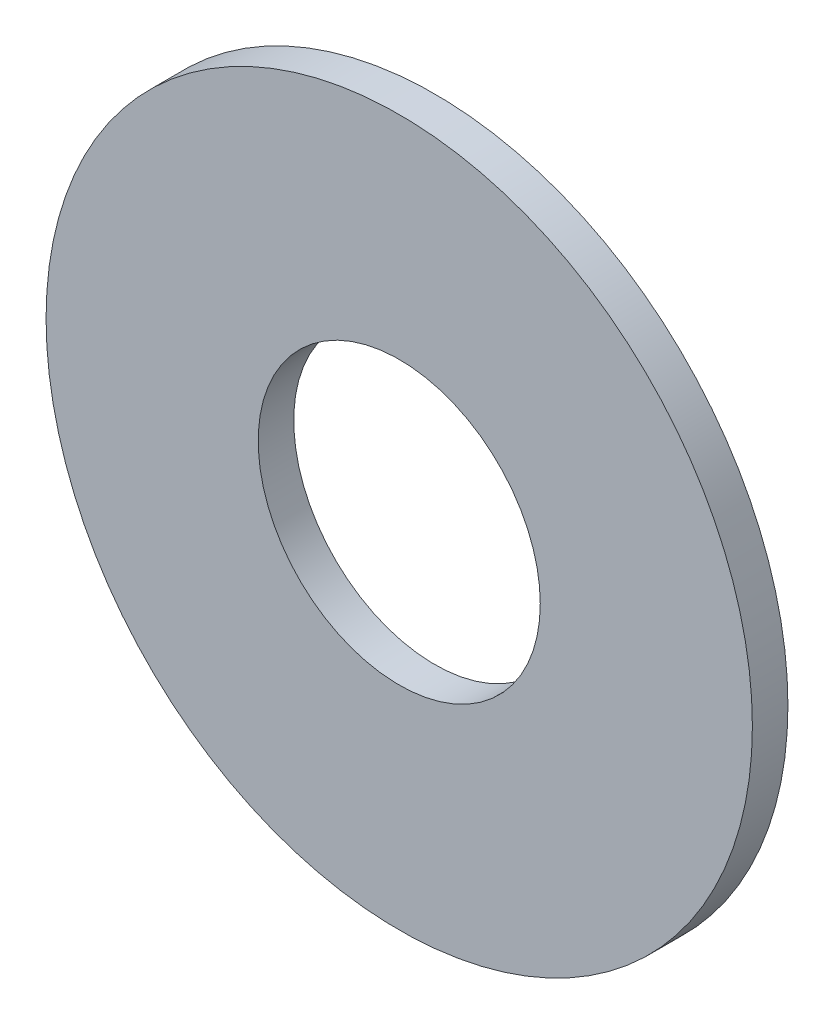
SolidWorks part; units mm, degrees
ref_plane "Front Plane" through (0, 0, 0) normal (0, 0, 1) x (1, 0, 0)
ref_plane "Top Plane" through (0, 0, 0) normal (0, 1, 0) x (1, 0, 0)
ref_plane "Right Plane" through (0, 0, 0) normal (1, 0, 0) x (0, 0, -1)
sketch "Sketch1" plane through (0, 0, 0) normal (0, 0, 1) x (1, 0, 0)
  circle A0 centre (0, 0) radius 1.5875
  circle A1 centre (0, 0) radius 3.975
  dimension "ID" = 3.175
  dimension "OD" = 7.95
extrude "Extrude1" add sketch "Sketch1" against normal blind 0.4
